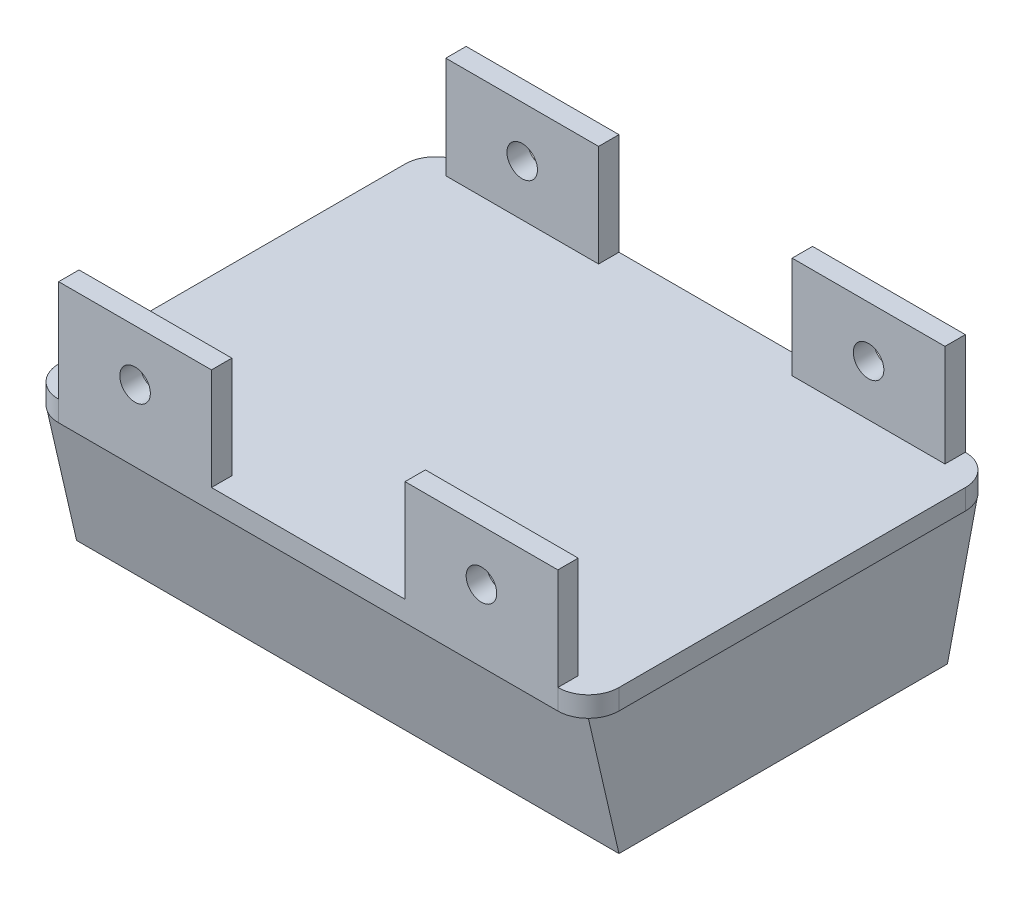
SolidWorks part; units mm, degrees
ref_plane "Front Plane" through (0, 0, 0) normal (0, 0, 1) x (1, 0, 0)
ref_plane "Top Plane" through (0, 0, 0) normal (0, 1, 0) x (1, 0, 0)
ref_plane "Right Plane" through (0, 0, 0) normal (1, 0, 0) x (0, 0, -1)
sketch "Sketch1" plane through (0, 0, 0) normal (0, 1, 0) x (1, 0, 0)
  line L1 (-45.3095, 16.369) -> (9.6905, 16.369)
  line L2 (-45.3095, 16.369) -> (-45.3095, -23.631)
  line L3 (-45.3095, -23.631) -> (9.6905, -23.631)
  line L4 (9.6905, 16.369) -> (9.6905, -23.631)
  dimension "D1" = 55
  dimension "D2" = 40
extrude "Boss-Extrude1" add sketch "Sketch1" along normal blind 2
sketch "Sketch3" plane through (0, 2, 0) normal (0, 1, 0) x (1, 0, 0)
  line L0 (-45.3095, -23.631) -> (9.6905, -23.631) construction
  line L1 (-45.3095, 16.369) -> (-42.3095, 16.369)
  line L2 (-45.3095, 16.369) -> (-45.3095, -23.631)
  line L3 (-45.3095, -23.631) -> (-42.3095, -23.631)
  line L4 (-42.3095, 16.369) -> (-42.3095, -23.631)
  line L5 (-17.8095, 16.369) -> (-17.8095, -23.631) construction
  line L6 (-42.3095, 16.369) -> (-27.3095, 16.369)
  line L7 (-42.3095, 16.369) -> (-42.3095, 14.369)
  line L8 (-42.3095, 14.369) -> (-27.3095, 14.369)
  line L9 (-27.3095, 16.369) -> (-27.3095, 14.369)
  line L10 (-42.3095, -23.631) -> (-27.3095, -23.631)
  line L11 (-42.3095, -23.631) -> (-42.3095, -21.631)
  line L12 (-42.3095, -21.631) -> (-27.3095, -21.631)
  line L13 (-27.3095, -23.631) -> (-27.3095, -21.631)
  line L14 (9.6905, 16.369) -> (-45.3095, 16.369) construction
  line L15 (-8.3095, -23.631) -> (-8.3095, -21.631)
  line L16 (6.6905, -21.631) -> (-8.3095, -21.631)
  line L17 (6.6905, -23.631) -> (6.6905, -21.631)
  line L18 (6.6905, -23.631) -> (-8.3095, -23.631)
  line L19 (-8.3095, 16.369) -> (-8.3095, 14.369)
  line L20 (6.6905, 14.369) -> (-8.3095, 14.369)
  line L21 (6.6905, 16.369) -> (6.6905, 14.369)
  line L22 (6.6905, 16.369) -> (-8.3095, 16.369)
  line L23 (6.6905, 16.369) -> (6.6905, -23.631)
  line L24 (9.6905, -23.631) -> (6.6905, -23.631)
  line L25 (9.6905, 16.369) -> (9.6905, -23.631)
  line L26 (9.6905, 16.369) -> (6.6905, 16.369)
  line M12 (-45.3095, -23.631) -> (9.6905, -23.631)
  line M14 (9.6905, 16.369) -> (-45.3095, 16.369)
  dimension "D1" = 3
  dimension "D2" = 15
  dimension "D3" = 2
  dimension "D4" = 2
extrude "Boss-Extrude2" add sketch "Sketch3" along normal blind 10 contours L9 L4 L8 M14 | L13 L12 L4 M12 | L17 L16 L15 M12 | L21 L19 L20 M14
fillet "Fillet1" radius 3 2 edges at (-43.8095, 2, -16.369) (-45.3095, 1, -16.369)
fillet "Fillet2" radius 3 2 edges at (-45.3095, 1, 23.631) (-43.8095, 2, 23.631)
fillet "Fillet3" radius 3 2 edges at (8.1905, 2, -16.369) (9.6905, 1, -16.369)
fillet "Fillet4" radius 3 2 edges at (8.1905, 2, 23.631) (9.6905, 1, 23.631)
sketch "Sketch4" plane through (0, 0, 23.631) normal (0, 0, 1) x (1, 0, 0)
  circle A0 centre (-0.8095, 7) radius 1.5
  circle A1 centre (-34.8095, 7) radius 1.5
extrude "Cut-Extrude1" cut sketch "Sketch4" against normal blind 50
sketch "Sketch5" plane through (0, 0, 0) normal (0, -1, 0) x (1, 0, 0)
  line L1 (-44.4308, 22.7523) -> (8.8118, 22.7523)
  line L2 (-44.4308, 22.7523) -> (-44.4308, -15.4904)
  line L3 (-44.4308, -15.4904) -> (8.8118, -15.4904)
  line L4 (8.8118, 22.7523) -> (8.8118, -15.4904)
  arc A0 (-42.3095, 23.631) -> (-45.3095, 20.631) centre (-42.3095, 20.631) ccw construction
  arc A1 (6.6905, -16.369) -> (9.6905, -13.369) centre (6.6905, -13.369) ccw construction
extrude "Boss-Extrude3" add sketch "Sketch5" along normal blind 13 contours L2 L1 L4 L3
sketch "Sketch6" plane through (-44.4308, 0, 0) normal (-1, 0, 0) x (0, 0, 1)
  line L0 (-15.4904, -13) -> (-12.4904, -13)
  line L1 (22.7523, -13) -> (-15.4904, -13) construction
  line L2 (-12.4904, -13) -> (-15.4904, 0)
  line L3 (3.631, 0) -> (3.631, -13) construction
  line L4 (22.7523, 0) -> (-15.4904, 0) construction
  line L5 (19.7523, -13) -> (22.7523, 0)
  line L6 (22.7523, -13) -> (19.7523, -13)
  line L7 (-15.4904, 0) -> (-15.4904, -13)
  line L8 (22.7523, 0) -> (22.7523, -13)
extrude "Cut-Extrude2" cut sketch "Sketch6" against normal through all contours L7 L0 L2 | L8 L6 L5
sketch "Sketch7" plane through (0, -13, 0) normal (0, -1, 0) x (1, 0, 0)
  circle A0 centre (-17.8095, 3.631) radius 0.75
extrude "Boss-Extrude4" add sketch "Sketch7" along normal blind 4
